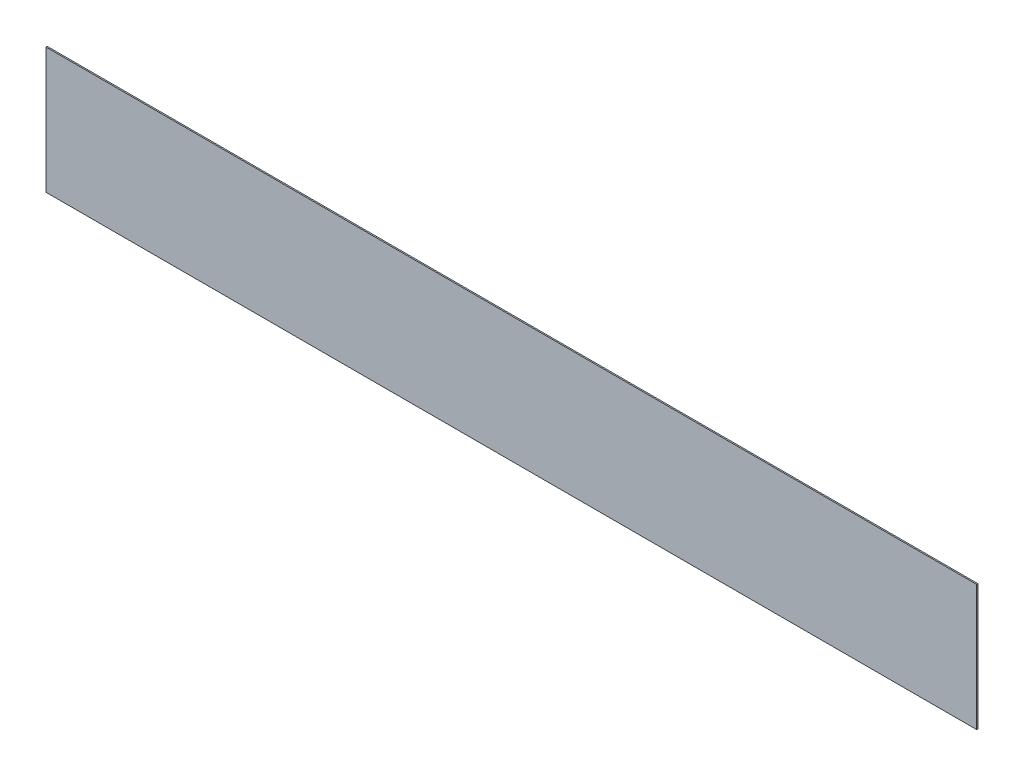
SolidWorks part; units mm, degrees
ref_plane "Спереди" through (0, 0, 0) normal (0, 0, 1) x (1, 0, 0)
ref_plane "Сверху" through (0, 0, 0) normal (0, 1, 0) x (1, 0, 0)
ref_plane "Справа" through (0, 0, 0) normal (1, 0, 0) x (0, 0, -1)
sketch "Sketch1" plane through (0, 0, 0) normal (0, 0, 1) x (1, 0, 0)
  line L1 (37, -5) -> (-37, -5)
  line L2 (37, -5) -> (37, 5)
  line L3 (37, 5) -> (-37, 5)
  line L4 (-37, -5) -> (-37, 5)
  line L5 (37, -5) -> (-37, 5) construction
  line L6 (37, 5) -> (-37, -5) construction
  point P0 (0, 0)
  dimension "D1" = 74
  dimension "D2" = 10
extrude "Boss-Extrude1" add sketch "Sketch1" along normal blind 0.1
